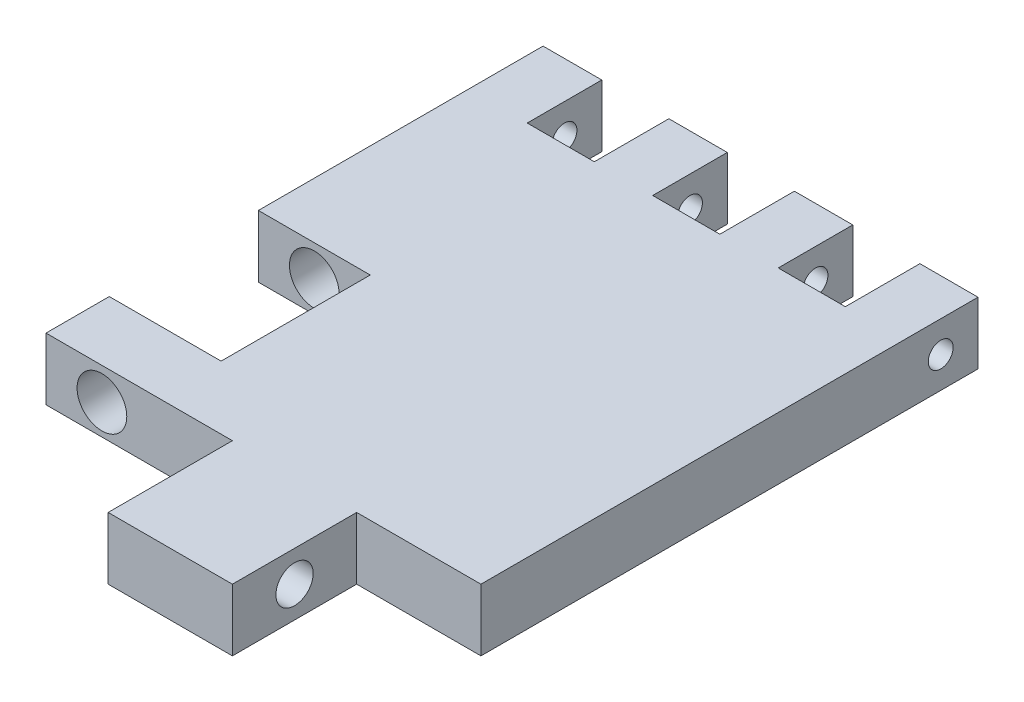
SolidWorks part; units mm, degrees
ref_plane "Front Plane" through (0, 0, 0) normal (0, 0, 1) x (1, 0, 0)
ref_plane "Top Plane" through (0, 0, 0) normal (0, 1, 0) x (1, 0, 0)
ref_plane "Right Plane" through (0, 0, 0) normal (1, 0, 0) x (0, 0, -1)
sketch "Sketch1" plane through (0, 0, 0) normal (0, 1, 0) x (1, 0, 0)
  line L0 (63.5, 0) -> (88.9, 0)
  line L1 (0, 0) -> (38.1, 0)
  line L2 (0, 0) -> (0, 101.6)
  line L3 (0, 101.6) -> (88.9, 101.6)
  line L4 (88.9, 0) -> (88.9, 101.6)
  line L6 (63.5, 0) -> (63.5, -25.4)
  line L7 (63.5, -25.4) -> (38.1, -25.4)
  line L8 (38.1, 0) -> (38.1, -25.4)
  dimension "D1" = 101.6
  dimension "D2" = 88.9
  dimension "D3" = 25.4
  dimension "D4" = 25.4
  dimension "D5" = 38.1
extrude "Boss-Extrude1" add sketch "Sketch1" along normal blind 12.7
sketch "Sketch3" plane through (0, 12.7, 0) normal (0, 1, 0) x (1, 0, 0)
  line L0 (88.9, 101.6) -> (0, 101.6) construction
  line L1 (12, 101.6) -> (25.716, 101.6)
  line L2 (12, 101.6) -> (12, 86.36)
  line L3 (12, 86.36) -> (25.716, 86.36)
  line L4 (25.716, 101.6) -> (25.716, 86.36)
  line L5 (0, 101.6) -> (0, 0) construction
  line L6 (37.654, 101.6) -> (51.37, 101.6)
  line L7 (37.654, 101.6) -> (37.654, 86.36)
  line L8 (37.654, 86.36) -> (51.37, 86.36)
  line L9 (51.37, 101.6) -> (51.37, 86.36)
  line L10 (63.308, 101.6) -> (77.024, 101.6)
  line L11 (63.308, 101.6) -> (63.308, 86.36)
  line L12 (63.308, 86.36) -> (77.024, 86.36)
  line L13 (77.024, 101.6) -> (77.024, 86.36)
  dimension "D1" = 13.716
  dimension "D2" = 12
  dimension "D3" = 15.24
  dimension "D4" = 3
extrude "Cut-Extrude1" cut sketch "Sketch3" against normal blind 12.7
sketch "Sketch4" plane through (0, 0, 0) normal (-1, 0, 0) x (0, 0, 1)
  line L0 (-86.36, 0) -> (-101.6, 0) construction
  line L1 (-101.6, 12.7) -> (-101.6, 0) construction
  line L2 (25.4, 12.7) -> (25.4, 0) construction
  line L3 (0, 12.7) -> (25.4, 12.7) construction
  circle A0 centre (-93.98, 6.35) radius 2.54
  circle A1 centre (12.7, 6.35) radius 3.81
  dimension "D2" = 5.08
  dimension "D4" = 7.62
  dimension "D5" = 12.7
  dimension "D6" = 6.35
  dimension "D1" = 6.35
  dimension "D3" = 7.62
extrude "Cut-Extrude2" cut sketch "Sketch4" against normal blind 91.44
sketch "Sketch7" plane through (0, 0, 0) normal (0, -1, 0) x (1, 0, 0)
  line L1 (0, -101.6) -> (0, 0) construction
  line L2 (22.86, -43.4129) -> (0, -43.4129)
  line L3 (22.86, -43.4129) -> (22.86, -12.9329)
  line L4 (22.86, -12.9329) -> (0, -12.9329)
  line L5 (0, -43.4129) -> (0, -12.9329)
  dimension "D1" = 22.86
  dimension "D2" = 30.48
extrude "Cut-Extrude10" cut sketch "Sketch7" against normal blind 18.288
sketch "Sketch8" plane through (0, 0, 0) normal (0, 0, 1) x (1, 0, 0)
  line L0 (0, 12.7) -> (0, 0) construction
  circle A0 centre (11.43, 6.1687) radius 5.08
  dimension "D2" = 10.16
  dimension "D1" = 11.43
extrude "Cut-Extrude12" cut sketch "Sketch8" against normal blind 54.61
